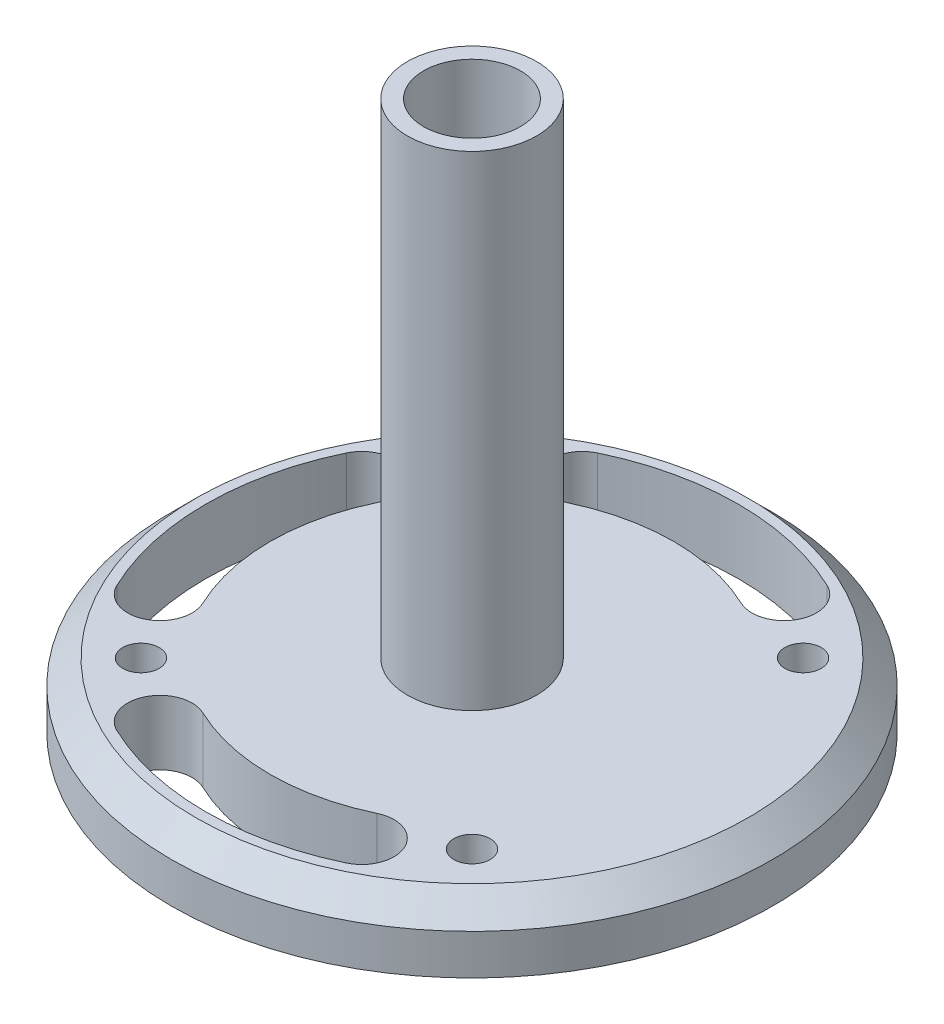
SolidWorks part; units mm, degrees
ref_plane "Front Plane" through (0, 0, 0) normal (0, 0, 1) x (1, 0, 0)
ref_plane "Top Plane" through (0, 0, 0) normal (0, 1, 0) x (1, 0, 0)
ref_plane "Right Plane" through (0, 0, 0) normal (1, 0, 0) x (0, 0, -1)
sketch "Sketch1" plane through (0, 0, 0) normal (0, 1, 0) x (1, 0, 0)
  circle A0 centre (0, 0) radius 37.25
  dimension "D1" = 74.5
extrude "Boss-Extrude1" add sketch "Sketch1" along normal blind 8
sketch "Sketch2" plane through (0, 8, 0) normal (0, 1, 0) x (1, 0, 0)
  circle A0 centre (0, 0) radius 8
  circle A1 centre (0, 0) radius 6
  dimension "D1" = 12
  dimension "D2" = 16
extrude "Boss-Extrude2" add sketch "Sketch2" along normal blind 60
chamfer "Chamfer1" distance 3 angle 45 1 edges at (0, 8, 37.25)
sketch "Sketch3" plane through (0, 8, 0) normal (0, 1, 0) x (1, 0, 0)
  circle A0 centre (0, 0) radius 6
extrude "Cut-Extrude1" cut sketch "Sketch3" against normal blind 10
sketch "Sketch4" plane through (0, 0, 0) normal (0, -1, 0) x (-1, 0, 0)
  line L0 (0, 0) -> (39.0913, 0) construction
  line L1 (26.1677, -12.5) -> (26.1677, 12.5) construction
  line L2 (26.1677, -12.5) -> (0, 0) construction
  line L3 (0, 0) -> (26.1677, 12.5) construction
  line L4 (0, 0) -> (32.6614, 32.6614) construction
  circle A0 centre (0, 0) radius 29
  arc A1 (26.1677, -12.5) -> (26.1677, 12.5) centre (0, 0) ccw
  arc A2 (26.1677, -12.5) -> (26.1677, 12.5) centre (0, 0) ccw construction
  arc A3 (29.7771, -14.2241) -> (29.7771, 14.2241) centre (0, 0) ccw
  arc A4 (22.5584, -10.7759) -> (22.5584, 10.7759) centre (0, 0) ccw
  arc A5 (22.5584, -10.7759) -> (29.7771, -14.2241) centre (26.1677, -12.5) ccw
  arc A6 (29.7771, 14.2241) -> (22.5584, 10.7759) centre (26.1677, 12.5) ccw
  arc A7 (-12.5, -26.1677) -> (12.5, -26.1677) centre (0, 0) ccw construction
  arc A8 (-14.2241, -29.7771) -> (14.2241, -29.7771) centre (0, 0) ccw
  arc A9 (-10.7759, -22.5584) -> (10.7759, -22.5584) centre (0, 0) ccw
  arc A10 (-10.7759, -22.5584) -> (-14.2241, -29.7771) centre (-12.5, -26.1677) ccw
  arc A11 (14.2241, -29.7771) -> (10.7759, -22.5584) centre (12.5, -26.1677) ccw
  arc A12 (-26.1677, 12.5) -> (-26.1677, -12.5) centre (0, 0) ccw construction
  arc A13 (-29.7771, 14.2241) -> (-29.7771, -14.2241) centre (0, 0) ccw
  arc A14 (-22.5584, 10.7759) -> (-22.5584, -10.7759) centre (0, 0) ccw
  arc A15 (-22.5584, 10.7759) -> (-29.7771, 14.2241) centre (-26.1677, 12.5) ccw
  arc A16 (-29.7771, -14.2241) -> (-22.5584, -10.7759) centre (-26.1677, -12.5) ccw
  arc A17 (12.5, 26.1677) -> (-12.5, 26.1677) centre (0, 0) ccw construction
  arc A18 (14.2241, 29.7771) -> (-14.2241, 29.7771) centre (0, 0) ccw
  arc A19 (10.7759, 22.5584) -> (-10.7759, 22.5584) centre (0, 0) ccw
  arc A20 (10.7759, 22.5584) -> (14.2241, 29.7771) centre (12.5, 26.1677) ccw
  arc A21 (-14.2241, 29.7771) -> (-10.7759, 22.5584) centre (-12.5, 26.1677) ccw
  circle A22 centre (20.5061, 20.5061) radius 2.25
  circle A23 centre (20.5061, -20.5061) radius 2.25
  circle A24 centre (-20.5061, -20.5061) radius 2.25
  circle A25 centre (-20.5061, 20.5061) radius 2.25
  point P5 (29, 0)
  point P16 (0, -29)
  point P23 (-29, 0)
  point P30 (0, 29)
  point P36 (0, 0)
  point P46 (0, 0)
  dimension "D1" = 25
  dimension "D2" = 58
  dimension "D3" = 4
  dimension "D4" = 4
  dimension "D6" = 4.5
  dimension "D5" = 45
  dimension "D7" = 4
extrude "Cut-Extrude2" cut sketch "Sketch4" against normal blind 10 contours A8 A11 A0 A10 | A0 A11 A9 A10 | A0 A6 A4 A5 | A3 A6 A0 A5 | A0 A21 A19 A20 | A18 A21 A0 A20 | A0 A23 | A0 A23 | A0 A22 | A0 A25 | A0 A25 | A0 A24 | A0 A24
